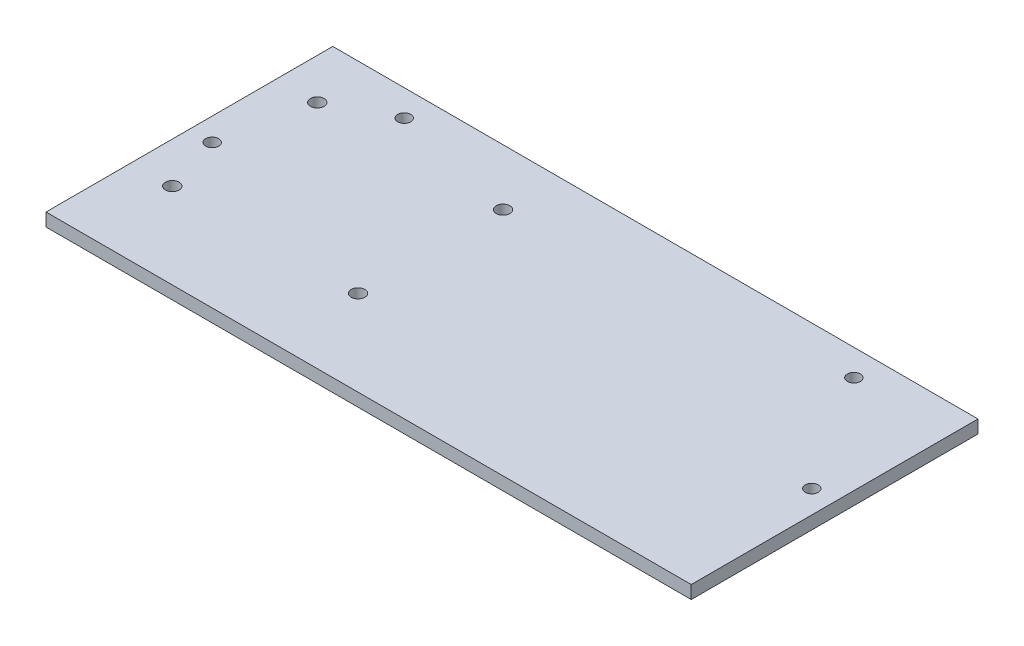
SolidWorks part; units mm, degrees
ref_plane "Front Plane" through (0, 0, 0) normal (0, 0, 1) x (1, 0, 0)
ref_plane "Top Plane" through (0, 0, 0) normal (0, 1, 0) x (1, 0, 0)
ref_plane "Right Plane" through (0, 0, 0) normal (1, 0, 0) x (0, 0, -1)
sketch "Sketch1" plane through (0, 0, 0) normal (0, 1, 0) x (1, 0, 0)
  line L1 (0, 0) -> (198, 0)
  line L2 (0, 0) -> (0, 88)
  line L3 (0, 88) -> (198, 88)
  line L4 (198, 0) -> (198, 88)
  dimension "D1" = 88
  dimension "D2" = 198
extrude "Boss-Extrude1" add sketch "Sketch1" along normal blind 4
sketch "Sketch2" plane through (0, 0, 0) normal (0, -1, 0) x (1, 0, 0)
  circle A0 centre (12.5, -26.25) radius 2.1
  circle A1 centre (69.5, -26.25) radius 2.1
  circle A2 centre (69.5, -70.75) radius 2.1
  circle A3 centre (12.5, -70.75) radius 2.1
extrude "Cut-Extrude1" cut sketch "Sketch2" against normal through all
sketch "Sketch3" plane through (0, 0, 0) normal (0, -1, 0) x (1, 0, 0)
  circle A0 centre (30, -79.9153) radius 2
  circle A1 centre (168, -79.9153) radius 2
extrude "Cut-Extrude2" cut sketch "Sketch3" against normal blind 10
sketch "Sketch4" plane through (0, 0, 0) normal (0, -1, 0) x (1, 0, 0)
  circle A0 centre (7, -44) radius 2
  circle A1 centre (191, -44) radius 2
extrude "Cut-Extrude3" cut sketch "Sketch4" against normal blind 25
